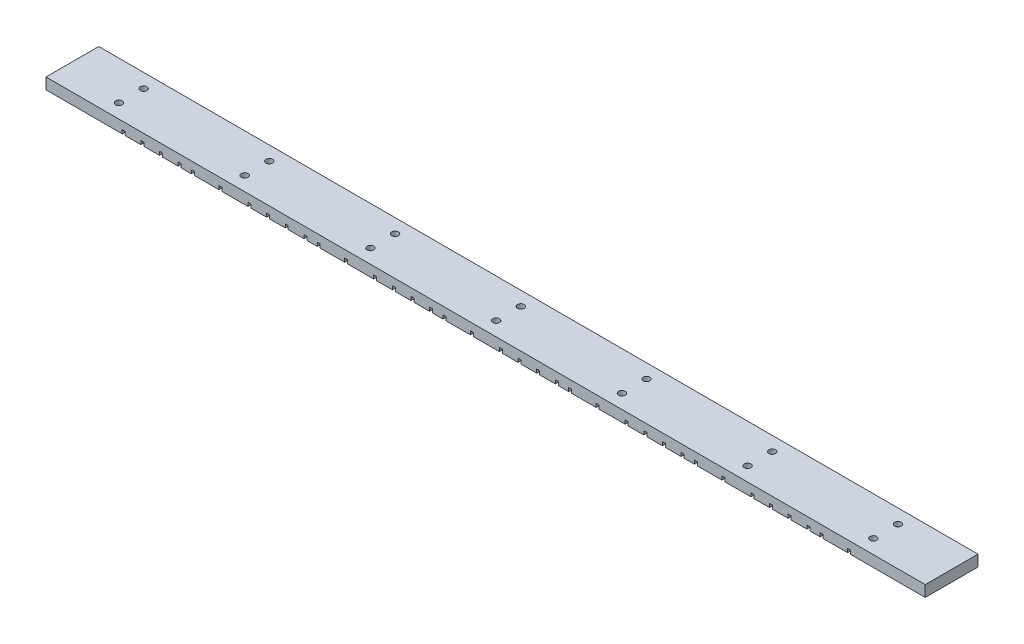
SolidWorks part; units mm, degrees
ref_plane "Front Plane" through (0, 0, 0) normal (0, 0, 1) x (1, 0, 0)
ref_plane "Top Plane" through (0, 0, 0) normal (0, 1, 0) x (1, 0, 0)
ref_plane "Right Plane" through (0, 0, 0) normal (1, 0, 0) x (0, 0, -1)
ref_plane "Plane1" through (0, 98, 0) normal (0, 1, 0) x (1, 0, 0)
sketch "Sketch2" plane through (0, 98, 0) normal (0, 1, 0) x (1, 0, 0)
  line L1 (-100, 50) -> (400, 50)
  line L2 (-100, 50) -> (-100, 20)
  line L3 (-100, 20) -> (400, 20)
  line L4 (400, 50) -> (400, 20)
extrude "Boss-Extrude1" add sketch "Sketch2" along normal blind 6.35
sketch "Sketch3" plane through (0, 98, 0) normal (0, 1, 0) x (1, 0, 0)
  circle A0 centre (362.5, 42) radius 3.175
  circle A1 centre (362.5, 28) radius 3.175
  circle A2 centre (291, 42) radius 3.175
  circle A3 centre (291, 28) radius 3.175
  circle A4 centre (219.5, 42) radius 3.175
  circle A5 centre (219.5, 28) radius 3.175
  circle A6 centre (148, 42) radius 3.175
  circle A7 centre (148, 28) radius 3.175
  circle A8 centre (76.5, 42) radius 3.175
  circle A9 centre (76.5, 28) radius 3.175
  circle A10 centre (5, 42) radius 3.175
  circle A11 centre (5, 28) radius 3.175
  circle A12 centre (-66.5, 42) radius 3.175
  circle A13 centre (-66.5, 28) radius 3.175
  dimension "D1" = 7
extrude "Cut-Extrude1" cut sketch "Sketch3" along normal blind 3
sketch "Sketch5" plane through (0, 0, -50) normal (0, 0, -1) x (-1, 0, 0)
  line L0 (-357.5571, 98) -> (-357.5571, 100.0571)
  line L1 (-357.5571, 100.0571) -> (-355.8553, 100.0571)
  line L2 (-355.8553, 100.0571) -> (-355.8553, 98)
  line L3 (-355.8553, 98) -> (-341.9571, 98)
  line L4 (-341.9571, 98) -> (-341.9571, 100.0571)
  line L5 (-341.9571, 100.0571) -> (-340.2553, 100.0571)
  line L6 (-340.2553, 100.0571) -> (-340.2553, 98)
  line L7 (-340.2553, 98) -> (-334.3571, 98)
  line L8 (-334.3571, 98) -> (-334.3571, 100.0571)
  line L9 (-334.3571, 100.0571) -> (-332.6553, 100.0571)
  line L10 (-332.6553, 100.0571) -> (-332.6553, 98)
  line L11 (-332.6553, 98) -> (-323.7571, 98)
  line L12 (-323.7571, 98) -> (-323.7571, 100.0571)
  line L13 (-323.7571, 100.0571) -> (-322.0554, 100.0571)
  line L14 (-322.0554, 100.0571) -> (-322.0554, 98)
  line L15 (-322.0554, 98) -> (-313.1572, 98)
  line L16 (-313.1572, 98) -> (-313.1572, 100.0571)
  line L17 (-313.1572, 100.0571) -> (-311.4554, 100.0571)
  line L18 (-311.4554, 100.0571) -> (-311.4554, 98)
  line L19 (-311.4554, 98) -> (-302.5571, 98)
  line L20 (-302.5571, 98) -> (-302.5571, 100.0571)
  line L21 (-302.5571, 100.0571) -> (-300.8554, 100.0571)
  line L22 (-300.8554, 100.0571) -> (-300.8554, 98)
  line L23 (-300.8554, 98) -> (-295.7895, 98)
  line L24 (-400, 98) -> (100, 98) construction
  line L25 (-295.7895, 98) -> (-295.7895, 96.6332)
  line L27 (-295.7895, 96.6332) -> (-359.0747, 96.6332)
  line L28 (-359.0747, 96.6332) -> (-359.0747, 98)
  line L29 (-359.0747, 98) -> (-357.5571, 98)
  line L30 (-286.0571, 98) -> (-286.0571, 100.0571)
  line L31 (-286.0571, 100.0571) -> (-284.3553, 100.0571)
  line L32 (-284.3553, 100.0571) -> (-284.3553, 98)
  line L33 (-284.3553, 98) -> (-270.4571, 98)
  line L34 (-270.4571, 98) -> (-270.4571, 100.0571)
  line L35 (-270.4571, 100.0571) -> (-268.7553, 100.0571)
  line L36 (-268.7553, 100.0571) -> (-268.7553, 98)
  line L37 (-268.7553, 98) -> (-262.8571, 98)
  line L38 (-262.8571, 98) -> (-262.8571, 100.0571)
  line L39 (-262.8571, 100.0571) -> (-261.1553, 100.0571)
  line L40 (-261.1553, 100.0571) -> (-261.1553, 98)
  line L41 (-261.1553, 98) -> (-252.2571, 98)
  line L42 (-252.2571, 98) -> (-252.2571, 100.0571)
  line L43 (-252.2571, 100.0571) -> (-250.5554, 100.0571)
  line L44 (-250.5554, 100.0571) -> (-250.5554, 98)
  line L45 (-250.5554, 98) -> (-241.6572, 98)
  line L46 (-241.6572, 98) -> (-241.6572, 100.0571)
  line L47 (-241.6572, 100.0571) -> (-239.9554, 100.0571)
  line L48 (-239.9554, 100.0571) -> (-239.9554, 98)
  line L49 (-239.9554, 98) -> (-231.0571, 98)
  line L50 (-231.0571, 98) -> (-231.0571, 100.0571)
  line L51 (-231.0571, 100.0571) -> (-229.3554, 100.0571)
  line L52 (-229.3554, 100.0571) -> (-229.3554, 98)
  line L53 (-229.3554, 98) -> (-224.2895, 98)
  line L54 (-224.2895, 98) -> (-224.2895, 96.6332)
  line L55 (-224.2895, 96.6332) -> (-287.5747, 96.6332)
  line L56 (-287.5747, 96.6332) -> (-287.5747, 98)
  line L57 (-287.5747, 98) -> (-286.0571, 98)
  line L58 (-214.5572, 98) -> (-214.5572, 100.0571)
  line L59 (-214.5572, 100.0571) -> (-212.8554, 100.0571)
  line L60 (-212.8554, 100.0571) -> (-212.8554, 98)
  line L61 (-212.8554, 98) -> (-198.9571, 98)
  line L62 (-198.9571, 98) -> (-198.9571, 100.0571)
  line L63 (-198.9571, 100.0571) -> (-197.2553, 100.0571)
  line L64 (-197.2553, 100.0571) -> (-197.2553, 98)
  line L65 (-197.2553, 98) -> (-191.3571, 98)
  line L66 (-191.3571, 98) -> (-191.3571, 100.0571)
  line L67 (-191.3571, 100.0571) -> (-189.6554, 100.0571)
  line L68 (-189.6554, 100.0571) -> (-189.6554, 98)
  line L69 (-189.6554, 98) -> (-180.7571, 98)
  line L70 (-180.7571, 98) -> (-180.7571, 100.0571)
  line L71 (-180.7571, 100.0571) -> (-179.0554, 100.0571)
  line L72 (-179.0554, 100.0571) -> (-179.0554, 98)
  line L73 (-179.0554, 98) -> (-170.1572, 98)
  line L74 (-170.1572, 98) -> (-170.1572, 100.0571)
  line L75 (-170.1572, 100.0571) -> (-168.4554, 100.0571)
  line L76 (-168.4554, 100.0571) -> (-168.4554, 98)
  line L77 (-168.4554, 98) -> (-159.5572, 98)
  line L78 (-159.5572, 98) -> (-159.5572, 100.0571)
  line L79 (-159.5572, 100.0571) -> (-157.8554, 100.0571)
  line L80 (-157.8554, 100.0571) -> (-157.8554, 98)
  line L81 (-157.8554, 98) -> (-152.7895, 98)
  line L82 (-152.7895, 98) -> (-152.7895, 96.6332)
  line L83 (-152.7895, 96.6332) -> (-216.0747, 96.6332)
  line L84 (-216.0747, 96.6332) -> (-216.0747, 98)
  line L85 (-216.0747, 98) -> (-214.5572, 98)
  line L86 (-143.0572, 98) -> (-143.0572, 100.0571)
  line L87 (-143.0572, 100.0571) -> (-141.3554, 100.0571)
  line L88 (-141.3554, 100.0571) -> (-141.3554, 98)
  line L89 (-141.3554, 98) -> (-127.4571, 98)
  line L90 (-127.4571, 98) -> (-127.4571, 100.0571)
  line L91 (-127.4571, 100.0571) -> (-125.7553, 100.0571)
  line L92 (-125.7553, 100.0571) -> (-125.7553, 98)
  line L93 (-125.7553, 98) -> (-119.8572, 98)
  line L94 (-119.8572, 98) -> (-119.8572, 100.0571)
  line L95 (-119.8572, 100.0571) -> (-118.1554, 100.0571)
  line L96 (-118.1554, 100.0571) -> (-118.1554, 98)
  line L97 (-118.1554, 98) -> (-109.2572, 98)
  line L98 (-109.2572, 98) -> (-109.2572, 100.0571)
  line L99 (-109.2572, 100.0571) -> (-107.5554, 100.0571)
  line L100 (-107.5554, 100.0571) -> (-107.5554, 98)
  line L101 (-107.5554, 98) -> (-98.6572, 98)
  line L102 (-98.6572, 98) -> (-98.6572, 100.0571)
  line L103 (-98.6572, 100.0571) -> (-96.9554, 100.0571)
  line L104 (-96.9554, 100.0571) -> (-96.9554, 98)
  line L105 (-96.9554, 98) -> (-88.0572, 98)
  line L106 (-88.0572, 98) -> (-88.0572, 100.0571)
  line L107 (-88.0572, 100.0571) -> (-86.3554, 100.0571)
  line L108 (-86.3554, 100.0571) -> (-86.3554, 98)
  line L109 (-86.3554, 98) -> (-81.2895, 98)
  line L110 (-81.2895, 98) -> (-81.2895, 96.6332)
  line L111 (-81.2895, 96.6332) -> (-144.5747, 96.6332)
  line L112 (-144.5747, 96.6332) -> (-144.5747, 98)
  line L113 (-144.5747, 98) -> (-143.0572, 98)
  line L114 (-71.5572, 98) -> (-71.5572, 100.0571)
  line L115 (-71.5572, 100.0571) -> (-69.8554, 100.0571)
  line L116 (-69.8554, 100.0571) -> (-69.8554, 98)
  line L117 (-69.8554, 98) -> (-55.9571, 98)
  line L118 (-55.9571, 98) -> (-55.9571, 100.0571)
  line L119 (-55.9571, 100.0571) -> (-54.2553, 100.0571)
  line L120 (-54.2553, 100.0571) -> (-54.2553, 98)
  line L121 (-54.2553, 98) -> (-48.3572, 98)
  line L122 (-48.3572, 98) -> (-48.3572, 100.0571)
  line L123 (-48.3572, 100.0571) -> (-46.6554, 100.0571)
  line L124 (-46.6554, 100.0571) -> (-46.6554, 98)
  line L125 (-46.6554, 98) -> (-37.7572, 98)
  line L126 (-37.7572, 98) -> (-37.7572, 100.0571)
  line L127 (-37.7572, 100.0571) -> (-36.0554, 100.0571)
  line L128 (-36.0554, 100.0571) -> (-36.0554, 98)
  line L129 (-36.0554, 98) -> (-27.1572, 98)
  line L130 (-27.1572, 98) -> (-27.1572, 100.0571)
  line L131 (-27.1572, 100.0571) -> (-25.4554, 100.0571)
  line L132 (-25.4554, 100.0571) -> (-25.4554, 98)
  line L133 (-25.4554, 98) -> (-16.5572, 98)
  line L134 (-16.5572, 98) -> (-16.5572, 100.0571)
  line L135 (-16.5572, 100.0571) -> (-14.8554, 100.0571)
  line L136 (-14.8554, 100.0571) -> (-14.8554, 98)
  line L137 (-14.8554, 98) -> (-9.7895, 98)
  line L138 (-9.7895, 98) -> (-9.7895, 96.6332)
  line L139 (-9.7895, 96.6332) -> (-73.0747, 96.6332)
  line L140 (-73.0747, 96.6332) -> (-73.0747, 98)
  line L141 (-73.0747, 98) -> (-71.5572, 98)
  line L142 (-0.0572, 98) -> (-0.0572, 100.0571)
  line L143 (-0.0572, 100.0571) -> (1.6446, 100.0571)
  line L144 (1.6446, 100.0571) -> (1.6446, 98)
  line L145 (1.6446, 98) -> (15.5429, 98)
  line L146 (15.5429, 98) -> (15.5429, 100.0571)
  line L147 (15.5429, 100.0571) -> (17.2447, 100.0571)
  line L148 (17.2447, 100.0571) -> (17.2447, 98)
  line L149 (17.2447, 98) -> (23.1428, 98)
  line L150 (23.1428, 98) -> (23.1428, 100.0571)
  line L151 (23.1428, 100.0571) -> (24.8446, 100.0571)
  line L152 (24.8446, 100.0571) -> (24.8446, 98)
  line L153 (24.8446, 98) -> (33.7428, 98)
  line L154 (33.7428, 98) -> (33.7428, 100.0571)
  line L155 (33.7428, 100.0571) -> (35.4446, 100.0571)
  line L156 (35.4446, 100.0571) -> (35.4446, 98)
  line L157 (35.4446, 98) -> (44.3428, 98)
  line L158 (44.3428, 98) -> (44.3428, 100.0571)
  line L159 (44.3428, 100.0571) -> (46.0446, 100.0571)
  line L160 (46.0446, 100.0571) -> (46.0446, 98)
  line L161 (46.0446, 98) -> (54.9428, 98)
  line L162 (54.9428, 98) -> (54.9428, 100.0571)
  line L163 (54.9428, 100.0571) -> (56.6446, 100.0571)
  line L164 (56.6446, 100.0571) -> (56.6446, 98)
  line L165 (56.6446, 98) -> (61.7105, 98)
  line L166 (61.7105, 98) -> (61.7105, 96.6332)
  line L167 (61.7105, 96.6332) -> (-1.5747, 96.6332)
  line L168 (-1.5747, 96.6332) -> (-1.5747, 98)
  line L169 (-1.5747, 98) -> (-0.0572, 98)
  dimension "D1" = 6
extrude "Cut-Extrude2" cut sketch "Sketch5" against normal through all
sketch "Sketch6" plane through (0, 104.35, 0) normal (0, 1, 0) x (1, 0, 0)
  circle A0 centre (-66.5, 28) radius 1.8987
  circle A1 centre (-66.5, 42) radius 1.8987
  circle A2 centre (-66.5, 28) radius 3.175 construction
  circle A3 centre (-66.5, 42) radius 3.175 construction
  circle A4 centre (5, 28) radius 1.8987
  circle A5 centre (5, 42) radius 1.8987
  circle A6 centre (76.5, 28) radius 1.8987
  circle A7 centre (76.5, 42) radius 1.8987
  circle A8 centre (148, 28) radius 1.8987
  circle A9 centre (148, 42) radius 1.8987
  circle A10 centre (219.5, 28) radius 1.8987
  circle A11 centre (219.5, 42) radius 1.8987
  circle A12 centre (291, 28) radius 1.8987
  circle A13 centre (291, 42) radius 1.8987
  circle A14 centre (362.5, 28) radius 1.8987
  circle A15 centre (362.5, 42) radius 1.8987
  dimension "D1" = 7
extrude "Cut-Extrude3" cut sketch "Sketch6" against normal through all
